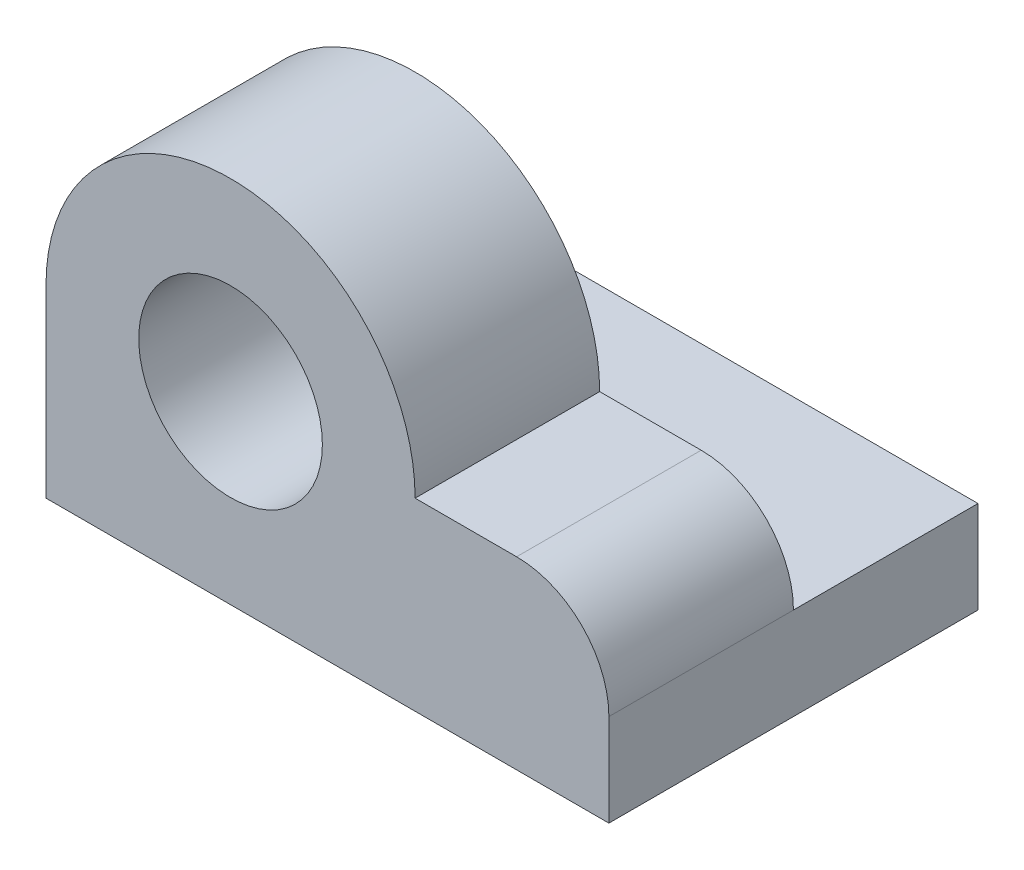
SolidWorks part; units mm, degrees
ref_plane "Front Plane" through (0, 0, 0) normal (0, 0, 1) x (1, 0, 0)
ref_plane "Top Plane" through (0, 0, 0) normal (0, 1, 0) x (1, 0, 0)
ref_plane "Right Plane" through (0, 0, 0) normal (1, 0, 0) x (0, 0, -1)
sketch "Sketch1" plane through (0, 0, 0) normal (1, 0, 0) x (0, 0, -1)
  line L0 (0, 0) -> (1016, 0)
  line L1 (1016, 0) -> (1016, 254)
  line L2 (1016, 254) -> (0, 254)
  line L3 (0, 254) -> (0, 0)
  dimension "D1" = 1016
  dimension "D2" = 254
extrude "Boss-Extrude1" add sketch "Sketch1" along normal blind 1549.4
sketch "Sketch2" plane through (0, 0, 0) normal (0, 0, 1) x (1, 0, 0)
  line L0 (0, 0) -> (0, 508)
  line L1 (1016, 508) -> (1295.4, 508)
  line L2 (0, 254) -> (0, 0) construction
  line L3 (1549.4, 0) -> (0, 0) construction
  line L4 (1549.4, 254) -> (1549.4, 0)
  circle A0 centre (508, 508) radius 252.73
  arc A1 (1016, 508) -> (0, 508) centre (508, 508) ccw
  arc A3 (1549.4, 254) -> (1295.4, 508) centre (1295.4, 254) ccw
  line M10 (1549.4, 254) -> (0, 254)
  dimension "D3" = 1295.4
  dimension "D4" = 1549.4
  dimension "D6" = 254
  dimension "D7" = 508
  dimension "D8" = 254
extrude "Boss-Extrude2" add sketch "Sketch2" against normal blind 508 contours A3 L1 A1 L0 A0 M10
